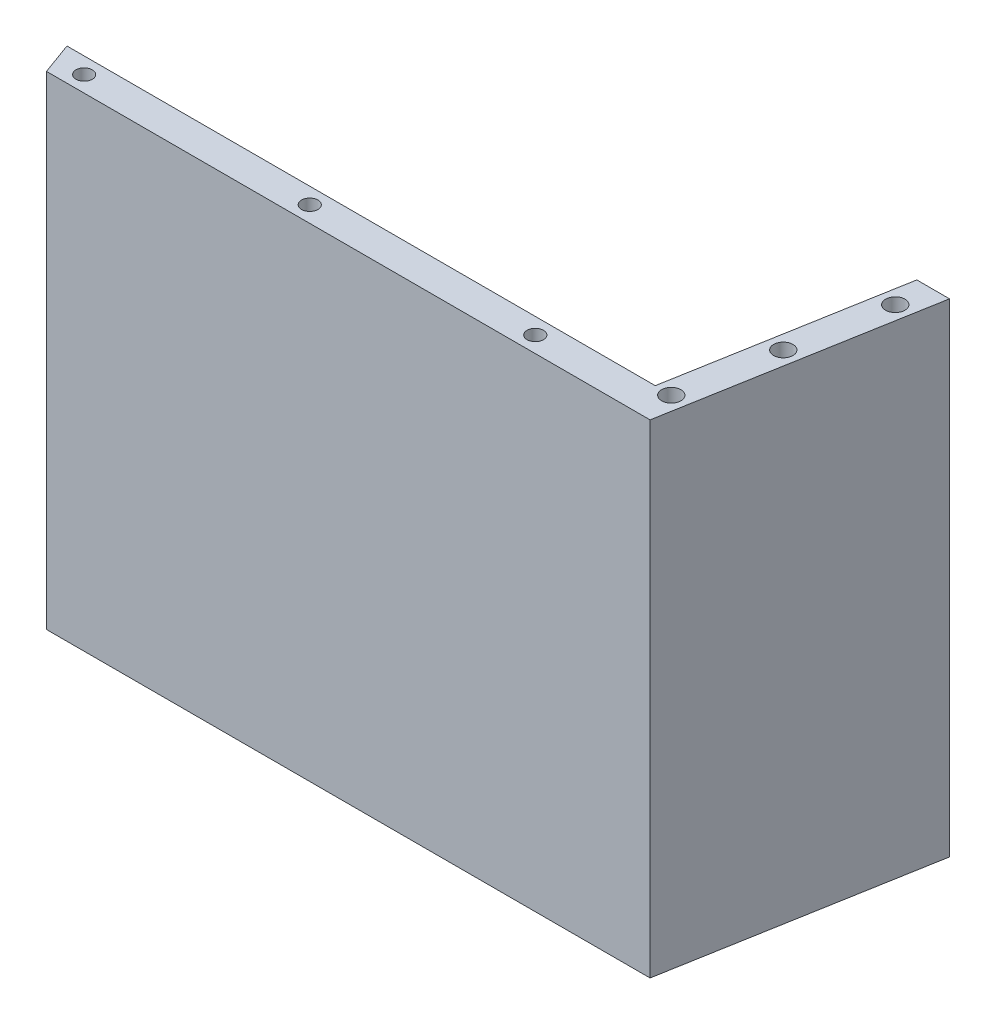
SolidWorks part; units mm, degrees
material "Custom Plastic"
ref_plane "Front Plane" through (0, 0, 0) normal (1, 0, 0) x (0, 1, 0)
ref_plane "Top Plane" through (0, 0, 0) normal (0, 0, 1) x (0, 1, 0)
ref_plane "Right Plane" through (0, 0, 0) normal (0, 1, 0) x (-1, 0, 0)
sketch "Sketch1" plane through (0, 0, 0) normal (0, 1, 0) x (-1, 0, 0)
  line L0 (-72.4911, -52.5) -> (42.5089, -52.5) construction
  line L1 (42.5089, -52.5) -> (28.1321, -13) construction
  line L2 (28.1321, -13) -> (-65.5261, -13)
  line L3 (-65.5261, -13) -> (-72.4911, -52.5)
  line L4 (29.952, -18) -> (-61.3306, -18)
  line L5 (-61.3306, -18) -> (-67.4139, -52.5)
  line L6 (-72.4911, -52.5) -> (-67.4139, -52.5)
  line L7 (28.1321, -13) -> (29.952, -18)
  arc A0 (-18.3644, -13) -> (18.3644, -13) centre (0, 0) ccw construction
  point P8 (-18.3644, -13)
  dimension "D1" = 45
  dimension "D2" = 115
  dimension "D3" = 13
  dimension "D4" = 80
  dimension "D5" = 70
  dimension "D6" = 13
  dimension "D7" = 28.1321
  dimension "D8" = 39.5
  dimension "D10" = 5
  dimension "D9" = 5
extrude "Boss-Extrude1" add sketch "Sketch1" along normal blind 37.5
sketch "Sketch2" plane through (0, 37.5, 0) normal (0, 1, 0) x (-1, 0, 0)
  line L0 (-72.4911, -52.5) -> (-67.4139, -52.5) construction
  line L1 (-71.6094, -47.5) -> (-66.5323, -47.5) construction
  line L2 (-65.5261, -13) -> (-72.4911, -52.5) construction
  line L3 (-67.4139, -52.5) -> (-61.3306, -18) construction
  line L4 (29.952, -18) -> (28.1321, -13) construction
  line L8 (28.1321, -13) -> (-65.5261, -13) construction
  circle A0 centre (-69.0709, -47.5) radius 1.5
  circle A1 centre (-66.4661, -32.7279) radius 1.5
  circle A2 centre (-63.8614, -17.9558) radius 1.5
  circle A7 centre (24.7853, -15.5) radius 1.2716
  circle A8 centre (-10.2147, -15.5) radius 1.2716
  circle A9 centre (-45.2147, -15.5) radius 1.2716
  dimension "D1" = 5
  dimension "D3" = 4
  dimension "D5" = 3
  dimension "D2" = 3
  dimension "D4" = 2.5
extrude "Cut-Extrude1" cut sketch "Sketch2" against normal blind 15 contours A9 | A8 | A7 | A0 | A1 | A2
mirror "Mirror1" about plane through (0, 0, 0) normal (0, -1, 0) of bodies 102
